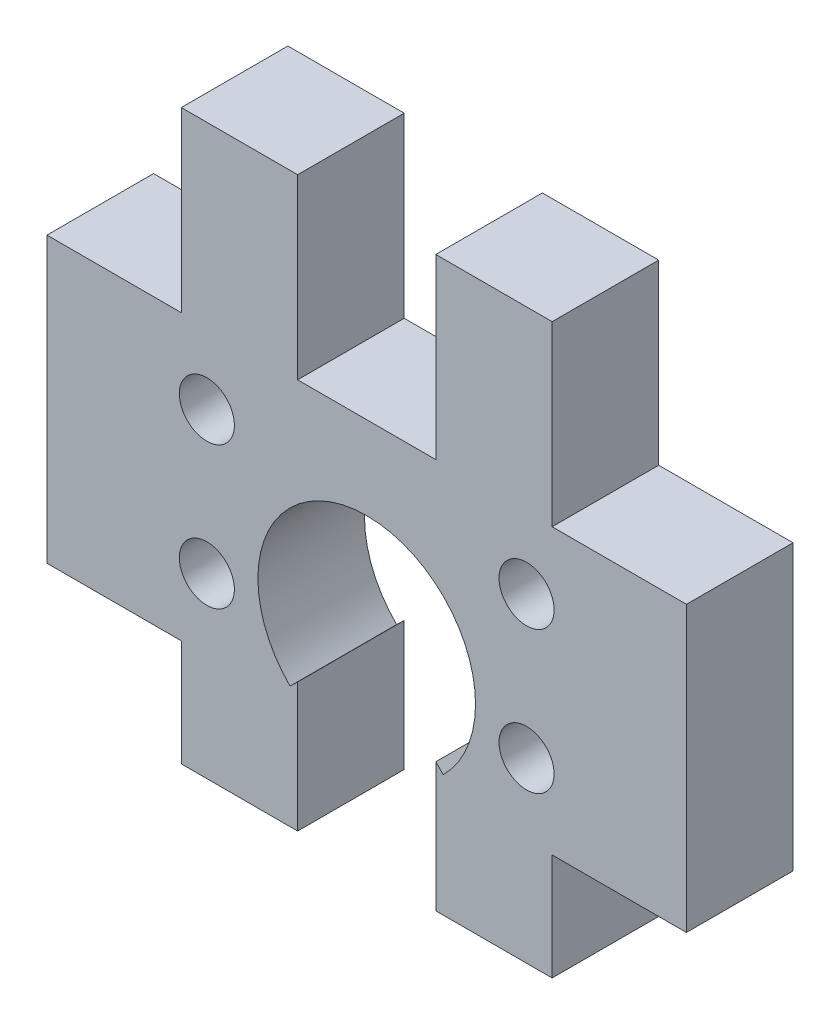
SolidWorks part; units mm, degrees
ref_plane "Płaszczyzna przednia" through (0, 0, 0) normal (0, 0, 1) x (1, 0, 0)
ref_plane "Płaszczyzna górna" through (0, 0, 0) normal (0, 1, 0) x (1, 0, 0)
ref_plane "Płaszczyzna prawa" through (0, 0, 0) normal (1, 0, 0) x (0, 0, -1)
sketch "Szkic1" plane through (0, 0, -64) normal (0, 0, 1) x (1, 0, 0)
  line L0 (71.503, 0) -> (35.503, 0)
  line L1 (71.503, 0) -> (71.503, -16)
  line L2 (35.503, 0) -> (35.503, -16)
  line L3 (71.503, -16) -> (35.503, -16)
  dimension "D1" = 36
  dimension "D2" = 16
extrude "Dodanie-wyciągnięcie1" add sketch "Szkic1" against normal blind 6
sketch "Szkic2" plane through (0, 0, -70) normal (0, 0, 1) x (1, 0, 0)
  line L0 (35.503, -16) -> (71.503, -16) construction
  line L1 (35.503, 0) -> (35.503, -16) construction
  line L2 (49.6145, -16) -> (49.6145, -14.7305)
  line L3 (35.503, -16) -> (71.503, -16) construction
  line L5 (57.3914, -16) -> (57.3914, -14.7305)
  line L6 (57.3914, -14.7305) -> (57.8128, -15.1521)
  line L7 (57.3914, -16) -> (49.6145, -16)
  line L9 (49.6145, -14.7305) -> (49.1868, -15.1458)
  arc A0 (57.9218, -15.0415) -> (49.0842, -15.0415) centre (53.503, -10.8) ccw
  arc A1 (57.9218, -15.0415) -> (57.8128, -15.1521) centre (53.503, -10.8) cw
  arc A2 (49.0842, -15.0415) -> (49.1868, -15.1458) centre (53.503, -10.8) ccw
  dimension "D1" = 5.2
  dimension "D2" = 12.25
  dimension "D3" = 18
  dimension "D4" = 3.8884
  dimension "D5" = 3.8884
  dimension "D6" = 0
extrude "Wytnij-wyciągnięcie1" cut sketch "Szkic2" along normal blind 6
sketch "Szkic3" plane through (0, 0, -70) normal (0, 0, -1) x (-1, 0, 0)
  line L0 (-57.3914, -16) -> (-71.503, -16) construction
  line L1 (-71.503, 0) -> (-35.503, 0) construction
  line L3 (-35.503, -16) -> (-49.6145, -16) construction
  circle A0 centre (-62.503, -4) radius 1.55
  circle A1 centre (-44.503, -4) radius 1.55
  circle A2 centre (-44.503, -12) radius 1.55
  circle A3 centre (-62.503, -12) radius 1.55
  arc A4 (-49.1868, -15.1458) -> (-57.8128, -15.1521) centre (-53.503, -10.8) ccw construction
  dimension "D1" = 4
  dimension "D2" = 4
  dimension "D4" = 4
  dimension "D5" = 9
  dimension "D6" = 9
  dimension "D7" = 9
  dimension "D8" = 9
  dimension "D9" = 3.1
  dimension "D10" = 3.1
  dimension "D11" = 3.1
  dimension "D12" = 3.1
extrude "Wytnij-wyciągnięcie2" cut sketch "Szkic3" against normal through all
sketch "Szkic5" plane through (0, -16, 0) normal (0, -1, 0) x (1, 0, 0)
  line L13 (57.3914, -70) -> (71.503, -70) construction
  line L14 (57.3914, -64) -> (63.9414, -64)
  line L15 (57.3914, -64) -> (57.3914, -70)
  line L16 (57.3914, -70) -> (63.9414, -70)
  line L17 (63.9414, -64) -> (63.9414, -70)
  line L18 (35.503, -70) -> (49.6145, -70) construction
  line L19 (49.6145, -64) -> (43.0645, -64)
  line L20 (49.6145, -64) -> (49.6145, -70)
  line L21 (49.6145, -70) -> (43.0645, -70)
  line L22 (43.0645, -64) -> (43.0645, -70)
  dimension "D1" = 6.55
  dimension "D2" = 6.55
extrude "Dodanie-wyciągnięcie2" add sketch "Szkic5" along normal blind 6 separate body
combine bodies "Połącz6" operation type add bodies to combine 104 105
sketch "Szkic7" plane through (0, 0, 0) normal (0, 1, 0) x (1, 0, 0)
  line L9 (57.3914, 64) -> (57.3914, 70) construction
  line L10 (57.3914, 70) -> (63.9414, 70) construction
  line L11 (63.9414, 70) -> (63.9414, 64) construction
  line L12 (63.9414, 64) -> (57.3914, 64) construction
  line L13 (49.6145, 70) -> (49.6145, 64) construction
  line L14 (49.6145, 64) -> (43.0645, 64) construction
  line L15 (43.0645, 64) -> (43.0645, 70) construction
  line L16 (43.0645, 70) -> (49.6145, 70) construction
  line L17 (57.3914, 64) -> (57.3914, 70)
  line L18 (57.3914, 70) -> (63.9414, 70)
  line L19 (63.9414, 70) -> (63.9414, 64)
  line L20 (63.9414, 64) -> (57.3914, 64)
  line L21 (49.6145, 70) -> (49.6145, 64)
  line L22 (49.6145, 64) -> (43.0645, 64)
  line L23 (43.0645, 64) -> (43.0645, 70)
  line L24 (43.0645, 70) -> (49.6145, 70)
extrude "Dodanie-wyciągnięcie3" add sketch "Szkic7" along normal blind 10
combine bodies "Połącz8" operation type add bodies to combine 112 111
equation "\"tolerancja_wpusy\"=0.2"
equation "\"dlugosc_wpustu_duzy\"=20"
equation "\"srednica_otworu_M3\"=3.1"
equation "\"szerokosc_nogi_T\"=3.1"
equation "\"dlugosc_T_30\"=11"
equation "\"grubosc_na_nakretke_kwadrat\"=2"
equation "\"szerokosc_na_nakretke_kwadrat\"=5.85"
equation "\"wyokosc_nadstawki_T\"=0.5"
equation "\"dlugosc_T_20_6\"=14"
equation "\"D9@Szkic3\"=\"srednica_otworu_M3\""
equation "\"D10@Szkic3\"=\"srednica_otworu_M3\""
equation "\"D11@Szkic3\"=\"srednica_otworu_M3\""
equation "\"D12@Szkic3\"=\"srednica_otworu_M3\""
